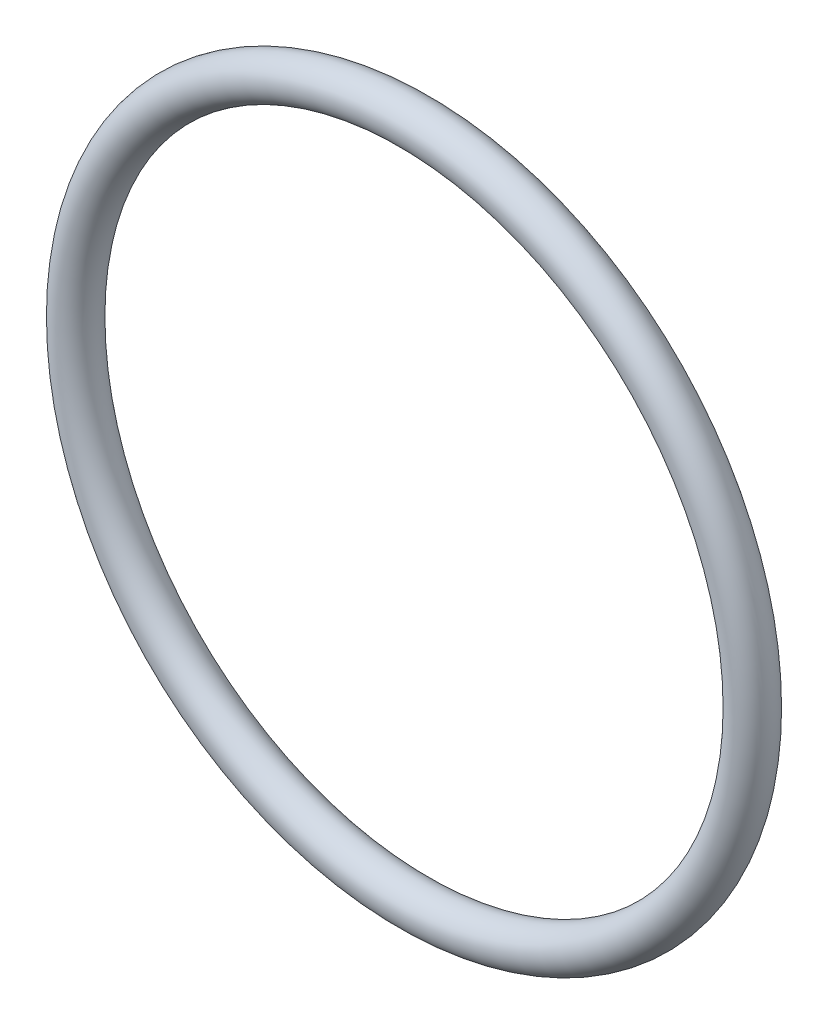
SolidWorks part; units mm, degrees
ref_plane "Front" through (0, 0, 0) normal (0, 0, 1) x (1, 0, 0)
ref_plane "Top" through (0, 0, 0) normal (0, 1, 0) x (1, 0, 0)
ref_plane "Right" through (0, 0, 0) normal (1, 0, 0) x (0, 0, -1)
sketch "Sketch1" plane through (0, 0, 0) normal (1, 0, 0) x (0, -1, 0)
  line L0 (0, -2.667) -> (0, 2.667) construction
  line L2 (-50.9206, 0) -> (50.9206, 0) construction
  line L3 (-40.9575, 0) -> (40.9575, 0) construction
  circle A0 centre (43.6245, 0) radius 2.667
  point P9 (40.9575, 0)
  point P10 (46.2915, 0)
  point P13 (43.6245, 2.667)
  point P14 (43.6245, -2.667)
  dimension "Width" = 5.334
  dimension "ID" = 81.915
revolve "Revolve1" add sketch "Sketch1" angle 360 about L0
